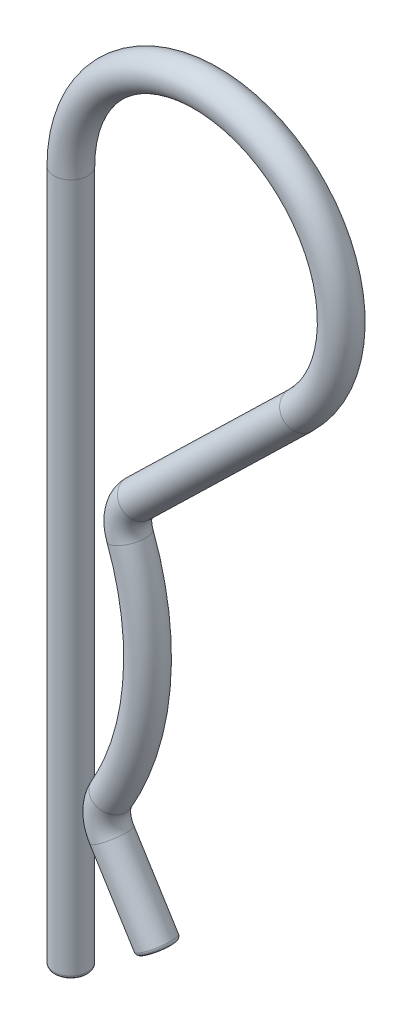
SolidWorks part; units mm, degrees
ref_plane "Спереди" through (0, 0, 0) normal (0, 0, 1) x (1, 0, 0)
ref_plane "Сверху" through (0, 0, 0) normal (0, 1, 0) x (1, 0, 0)
ref_plane "Справа" through (0, 0, 0) normal (1, 0, 0) x (0, 0, -1)
sketch "Эскиз1" plane through (0, 0, 0) normal (0, 0, 1) x (1, 0, 0)
  line L0 (-8, 0) -> (-8, -41)
  line L1 (-31.0207, -16) -> (22.9092, -16) construction
  line L2 (5.5714, -5.7411) -> (-4.0244, -15.0532)
  line L3 (-31.0207, -32) -> (22.9092, -32) construction
  line L4 (-5.5754, -33.0581) -> (-2.8297, -37.4621)
  arc A0 (5.5714, -5.7411) -> (-8, 0) centre (0, 0) ccw
  arc A1 (-5.6136, -31.0057) -> (-4.5034, -17.1929) centre (-19.7252, -22.9205) ccw
  arc A2 (-5.6136, -31.0057) -> (-5.5754, -33.0581) centre (-3.8782, -32) ccw
  arc A3 (-4.0244, -15.0532) -> (-4.5034, -17.1929) centre (-2.6316, -16.4885) ccw
  point P13 (-6.2318, -32)
  dimension "D1" = 16
  dimension "D6" = 4
  dimension "D7" = 4
  dimension "D2" = 41
  dimension "D3" = 25
  dimension "D5" = 9
ref_plane "Плоскость1" through (-8, -41, 0) normal (0, -1, 0) x (-1, 0, 0)
sketch "Эскиз2" plane through (-8, -41, 0) normal (0, -1, 0) x (-1, 0, 0)
  line L0 (-16, 0) -> (0, 0) construction
  line L1 (23.0207, 0) -> (-30.9092, 0) construction
  circle A0 centre (0, 0) radius 1
  dimension "D1" = 2
sweep "По траектории1" add profiles "Эскиз2" path "Эскиз1"
fillet "Скругление1" radius 0.2 2 edges at (-3.6783, -37.9912, 0) (-7, -41, 0)
